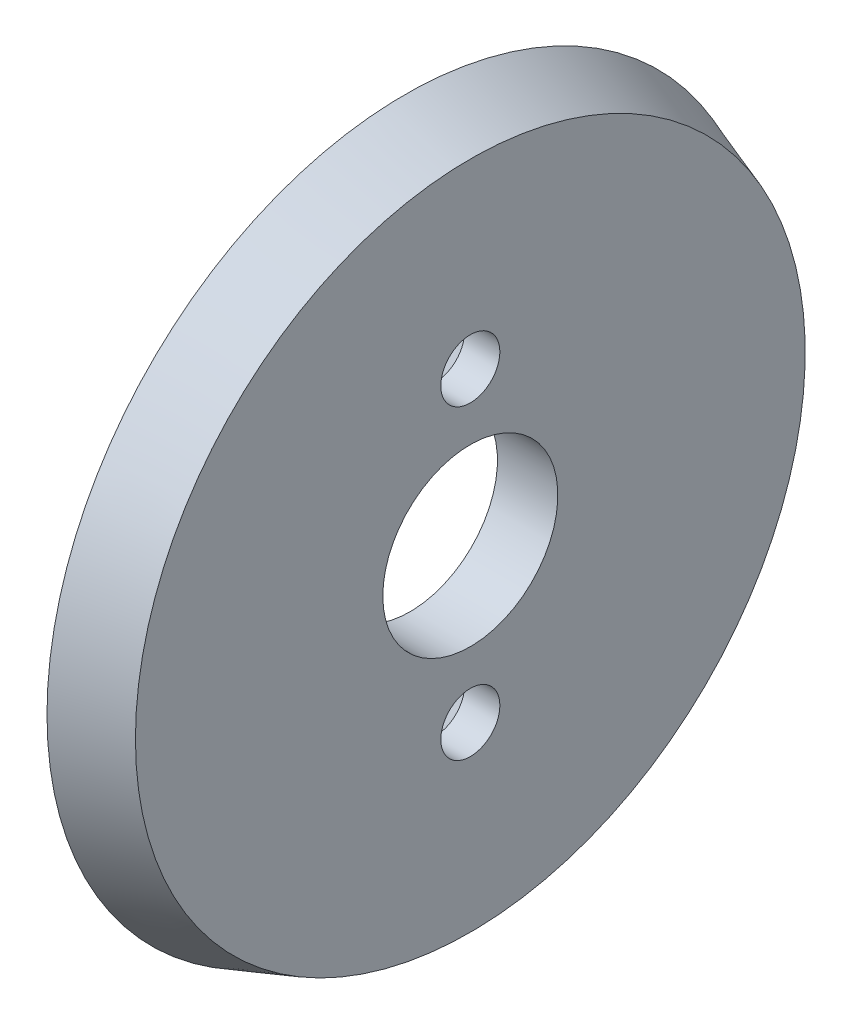
SolidWorks part; units mm, degrees
ref_plane "Front Plane" through (0, 0, 0) normal (0, 0, 1) x (1, 0, 0)
ref_plane "Top Plane" through (0, 0, 0) normal (0, 1, 0) x (1, 0, 0)
ref_plane "Right Plane" through (0, 0, 0) normal (1, 0, 0) x (0, 0, -1)
ref_plane "Plane1" through (0, 0, 0) normal (0, 0, -1) x (-1, 0, 0)
sketch "Sketch1" plane through (0, 0, 0) normal (0, 0, -1) x (-1, 0, 0)
  line L1 (-9.95, 4) -> (-7.1906, 4)
  line L2 (-7.1906, 4) -> (-7.1906, 11.4579)
  line L3 (-7.1906, 11.4579) -> (-5.45, 12.0707)
  line L4 (-5.45, 12.0707) -> (-6.96, 16.36)
  line L5 (-6.96, 16.36) -> (-9.95, 15.3074)
  line L6 (-9.95, 15.3074) -> (-9.95, 4)
  line L9 (-15.4765, 0) -> (0, 0) construction
  point P0 (0, 0)
  dimension "D1" = 2.99
  dimension "D2" = 4.5
  dimension "D3" = 0
  dimension "D4" = 16.36
  dimension "D5" = 9.95
  dimension "D6" = 4
revolve "Revolve1" add sketch "Sketch1" angle 360 about L9
sketch "Sketch2" plane through (7.1906, 0, 0) normal (-1, 0, 0) x (0, 0, 1)
  point P0 (0, 7)
  point P2 (0, -7)
  point P4 (0, 0)
  point P5 (0, 0)
  point P6 (0, 0)
  point P9 (0, 0)
  point P10 (0, 0)
  point P11 (0, 0)
hole_wizard "CSK for M3 Flat Countersunk Head Screw1" positions "Sketch2" profile "Sketch3" countersink size "M3" standard "JIS" end condition up to next
sketch "Sketch3" plane through (7.1906, 7, 0) normal (0, 1, 0) x (0, 0, 1)
  line L0 (0, 0) -> (0, 2.7594)
  line L1 (0, 2.7594) -> (1.35, 2.7594)
  line L2 (1.35, 2.7594) -> (1.35, 1.15)
  line L3 (1.35, 1.15) -> (2.5, 0)
  line L5 (2.5, 0) -> (0, 0)
  line L6 (-1.35, 1.15) -> (-2.5, 0) construction
  line L11 (0, -6.35) -> (0, 107.95) construction
  dimension "Thru Hole Dia." = 2.7
  dimension "Thru Hole Depth" = 2.7594
  dimension "Near C'Sink Dia." = 5
  dimension "Near C'Sink Angle" = 90
